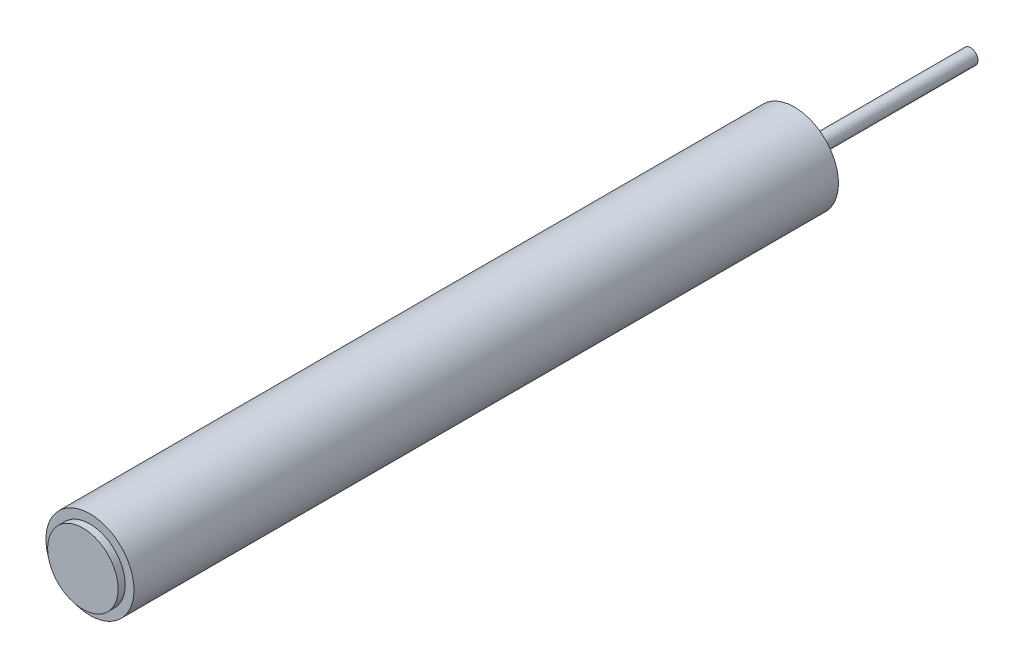
SolidWorks part; units mm, degrees
ref_plane "Front Plane" through (0, 0, 0) normal (0, 0, 1) x (1, 0, 0)
ref_plane "Top Plane" through (0, 0, 0) normal (0, 1, 0) x (1, 0, 0)
ref_plane "Right Plane" through (0, 0, 0) normal (1, 0, 0) x (0, 0, -1)
sketch "Sketch1" plane through (0, 0, 0) normal (0, 0, 1) x (1, 0, 0)
  circle A0 centre (0, 0) radius 3.175
  circle A1 centre (0, 0) radius 2.54
  dimension "D1" = 6.35
  dimension "D2" = 5.08
extrude "Boss-Extrude1" add sketch "Sketch1" along normal blind 50.8
sketch "Sketch2" plane through (0, 0, 50.8) normal (0, 0, 1) x (1, 0, 0)
  circle A0 centre (0, 0) radius 2.54
extrude "Boss-Extrude2" add sketch "Sketch2" against normal blind 2.54 and the other way blind 0.508
ref_plane "Plane1" through (0, 0, 0) normal (0, 0, -1) x (-1, 0, 0)
sketch "Sketch3" plane through (0, 0, 0) normal (0, 0, -1) x (-1, 0, 0)
  circle A0 centre (0, 0) radius 0.5371
extrude "Boss-Extrude3" add sketch "Sketch3" along normal blind 60.96 from surface at -48.26 starting at face at (2.54, 0, 48.26)
